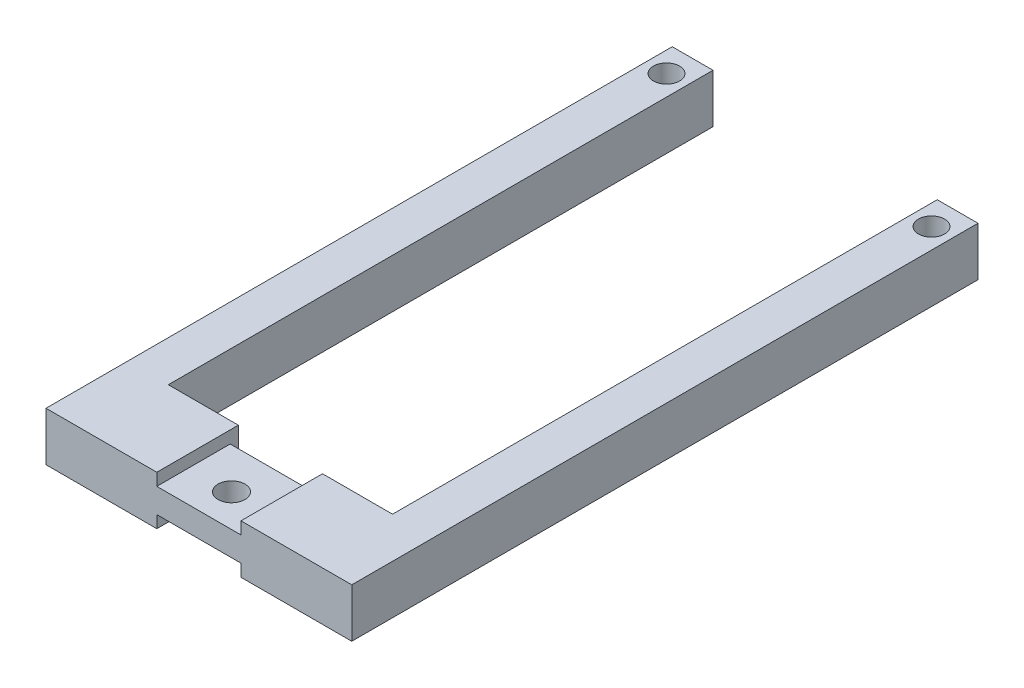
SolidWorks part; units mm, degrees
ref_plane "Front Plane" through (0, 0, 0) normal (0, 0, 1) x (1, 0, 0)
ref_plane "Top Plane" through (0, 0, 0) normal (0, 1, 0) x (1, 0, 0)
ref_plane "Right Plane" through (0, 0, 0) normal (1, 0, 0) x (0, 0, -1)
sketch "Sketch1" plane through (0, 0, 0) normal (0, 1, 0) x (1, 0, 0)
  line L0 (-37.8907, -44.4315) -> (-30.5507, -44.4315)
  line L1 (-12.8907, -44.4315) -> (-12.8907, 4.4685)
  line L2 (-42.8907, -54.4315) -> (-7.8907, -54.4315)
  line L3 (-7.8907, -54.4315) -> (-7.8907, 4.4685)
  line L4 (-37.8907, -44.4315) -> (-37.8907, 4.4685)
  line L5 (-42.8907, -54.4315) -> (-42.8907, 4.4685)
  line L6 (-30.5507, -44.4315) -> (-30.5507, -45.4315)
  line L7 (-30.5507, -45.4315) -> (-20.2307, -45.4315)
  line L8 (-20.2307, -45.4315) -> (-20.2307, -44.4315)
  line L9 (-20.2307, -44.4315) -> (-12.8907, -44.4315)
  line L10 (-42.8907, 4.4685) -> (-37.8907, 4.4685)
  line L11 (-12.8907, 4.4685) -> (-7.8907, 4.4685)
  circle A0 centre (-25.3907, -50.4315) radius 1.65
  point P14 (-25.3907, -45.4315)
  dimension "D2" = 35
  dimension "D8" = 5
  dimension "D9" = 3.3
  dimension "D1" = 10.32
  dimension "D3" = 25
  dimension "D4" = 5
  dimension "D5" = 1
  dimension "D6" = 58.9
  dimension "D7" = 10
extrude "Boss-Extrude1" add sketch "Sketch1" along normal blind 8
sketch "Sketch2" plane through (0, 8, 0) normal (0, 1, 0) x (1, 0, 0)
  line L0 (-30.5507, -45.4315) -> (-30.5507, -54.4315)
  line L1 (-42.8907, -54.4315) -> (-7.8907, -54.4315) construction
  line L2 (-30.5507, -54.4315) -> (-20.2307, -54.4315)
  line L3 (-20.2307, -54.4315) -> (-20.2307, -45.4315)
  line L4 (-20.2307, -45.4315) -> (-30.5507, -45.4315)
extrude "Cut-Extrude1" cut sketch "Sketch2" against normal blind 2.4
sketch "Sketch3" plane through (0, 0, 0) normal (0, -1, 0) x (1, 0, 0)
  line L0 (-30.5507, 45.4315) -> (-30.5507, 54.4315)
  line L1 (-42.8907, 54.4315) -> (-7.8907, 54.4315) construction
  line L2 (-30.5507, 54.4315) -> (-20.2307, 54.4315)
  line L3 (-20.2307, 54.4315) -> (-20.2307, 45.4315)
  line L4 (-20.2307, 45.4315) -> (-30.5507, 45.4315)
extrude "Cut-Extrude2" cut sketch "Sketch3" against normal blind 2.4
sketch "Sketch5" plane through (0, 8, 0) normal (0, 1, 0) x (1, 0, 0)
  line L8 (-25.3907, -45.4315) -> (-25.3907, 12.8323) construction
  line L10 (-32.3907, 4.4685) -> (-18.3907, 4.4685)
  point P17 (-25.3907, 4.4685)
sketch "Sketch6" plane through (0, 0, 0) normal (0, -1, 0) x (1, 0, 0)
  line L2 (-37.8907, -22.3685) -> (-37.8907, -4.4685)
  line L5 (-25.3907, -4.4685) -> (-25.3907, -14.1361) construction
  line L6 (-25.3907, 200045.4315) -> (-25.3907, -200012.8323) construction
  line L11 (-44.8907, -10.7685) -> (-44.8907, -22.3685)
  line L13 (-44.8907, -22.3685) -> (-37.8907, -22.3685)
  line L16 (-44.8907, -10.7685) -> (-44.8907, 54.4315)
  line L19 (-37.8907, 44.4315) -> (-37.8907, -4.4685) construction
  line L20 (-44.8907, 54.4315) -> (-42.8907, 54.4315)
  line L21 (-42.8907, 54.4315) -> (-42.8907, -4.4685)
  line L22 (-42.8907, -4.4685) -> (-37.8907, -4.4685)
  line L23 (-7.8907, -4.4685) -> (-12.8907, -4.4685)
  line L24 (-7.8907, 54.4315) -> (-7.8907, -4.4685)
  line L25 (-5.8907, 54.4315) -> (-7.8907, 54.4315)
  line L26 (-5.8907, -10.7685) -> (-5.8907, 54.4315)
  line L27 (-5.8907, -22.3685) -> (-12.8907, -22.3685)
  line L28 (-5.8907, -10.7685) -> (-5.8907, -22.3685)
  line L29 (-12.8907, -22.3685) -> (-12.8907, -4.4685)
  dimension "D1" = 17.9
  dimension "D5" = 7
extrude "Boss-Extrude2" add sketch "Sketch6" against normal up to surface (8 mm away) up to face at (-37.1107, 8, 31.4648)
sketch "Sketch7" plane through (-5.8907, 0, 0) normal (1, 0, 0) x (0, 0, -1)
  line L0 (-54.4315, 8) -> (-54.4315, 7)
  line L1 (22.3685, 0) -> (-54.4315, 0) construction
  line L2 (-54.4315, 7) -> (22.3685, 7)
  line L3 (-54.4315, 8) -> (-54.4315, 0) construction
  line L4 (22.3685, 7) -> (22.3685, 8)
  line L5 (22.3685, 8) -> (-54.4315, 8)
  line L6 (-54.4315, 0) -> (-54.4315, 1)
  line L7 (-54.4315, 1) -> (22.3685, 1)
  line L8 (22.3685, 1) -> (22.3685, 0)
  line L9 (22.3685, 0) -> (-54.4315, 0)
  line L10 (22.3685, 8) -> (22.3685, 0) construction
  dimension "D1" = 1
extrude "Cut-Extrude3" cut sketch "Sketch7" against normal through all
sketch "Sketch9" plane through (0, 0, 54.4315) normal (0, 0, 1) x (1, 0, 0)
  line L0 (-30.5507, 5.6) -> (-30.5507, 5.5)
  line L1 (-30.5507, 5.5) -> (-20.2307, 5.5)
  line L2 (-20.2307, 5.5) -> (-20.2307, 5.6)
  line L3 (-20.2307, 5.6) -> (-30.5507, 5.6)
  line L4 (-30.5507, 2.4) -> (-30.5507, 2.5)
  line L5 (-30.5507, 2.5) -> (-20.2307, 2.5)
  line L6 (-20.2307, 2.5) -> (-20.2307, 2.4)
  line L7 (-20.2307, 2.4) -> (-30.5507, 2.4)
  dimension "D1" = 0.1
  dimension "D2" = 0.1
extrude "Cut-Extrude4" cut sketch "Sketch9" against normal blind 10
sketch "Sketch10" plane through (0, 7, 0) normal (0, 1, 0) x (1, 0, 0)
  line L0 (-37.8907, 22.3685) -> (-39.1407, 22.3685)
  line L1 (-39.1407, 22.3685) -> (-39.1407, -44.4315)
  line L2 (-39.1407, -44.4315) -> (-37.8907, -44.4315)
  line L3 (-37.8907, -44.4315) -> (-30.5507, -44.4315) construction
  line L4 (-37.8907, 22.3685) -> (-37.8907, -44.4315)
  line L5 (-25.3907, 4.4685) -> (-25.3907, -27.9577) construction
  line L6 (-32.3907, 4.4685) -> (-18.3907, 4.4685) construction
  line L7 (-25.3907, -200045.4315) -> (-25.3907, 200012.8323) construction
  line L8 (-12.8907, 22.3685) -> (-12.8907, -44.4315)
  line L9 (-11.6407, -44.4315) -> (-12.8907, -44.4315)
  line L10 (-11.6407, 22.3685) -> (-11.6407, -44.4315)
  line L11 (-12.8907, 22.3685) -> (-11.6407, 22.3685)
  line L14 (-44.8907, 22.3685) -> (-37.8907, 22.3685) construction
  line L15 (-39.1407, 22.3685) -> (-44.1407, 22.3685) construction
  line L17 (-5.8907, -54.4315) -> (-6.6407, -54.4315)
  line L18 (-44.8907, 22.3685) -> (-44.1407, 22.3685)
  line L19 (-44.8907, 22.3685) -> (-44.8907, -54.4315)
  line L20 (-44.8907, -54.4315) -> (-44.1407, -54.4315)
  line L21 (-44.1407, 22.3685) -> (-44.1407, -54.4315)
  line L22 (-5.8907, 22.3685) -> (-5.8907, -54.4315)
  line L23 (-5.8907, 22.3685) -> (-6.6407, 22.3685)
  line L24 (-6.6407, 22.3685) -> (-6.6407, -54.4315)
  circle A0 centre (-41.6407, 19.1685) radius 1.6
  circle A1 centre (-9.1407, 19.1685) radius 1.6
  point P25 (-41.6407, 22.3685)
  dimension "D2" = 3.2
  dimension "D1" = 1.25
  dimension "D3" = 3.2
  dimension "D4" = 0.75
extrude "Cut-Extrude5" cut sketch "Sketch10" against normal up to surface (6 mm away) up to face at (-37.7773, 1, 25.4982)
